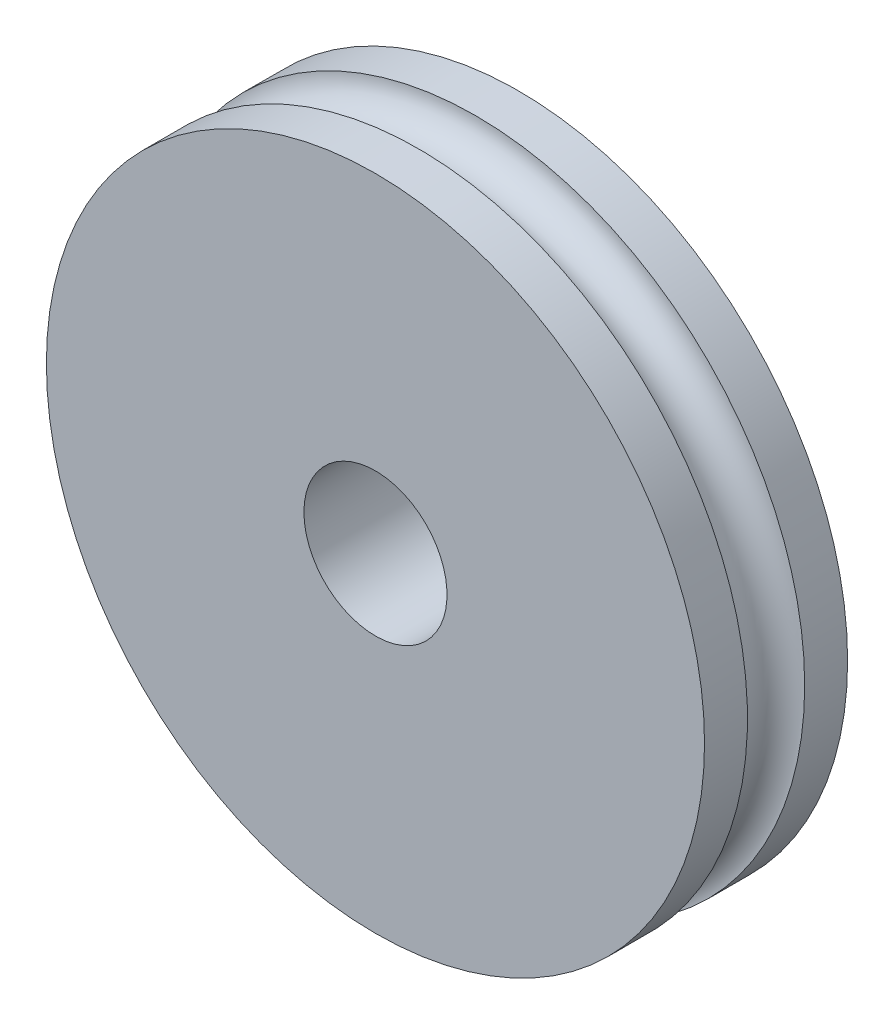
SolidWorks part; units mm, degrees
ref_plane "Front Plane" through (0, 0, 0) normal (0, 0, 1) x (1, 0, 0)
ref_plane "Top Plane" through (0, 0, 0) normal (0, 1, 0) x (1, 0, 0)
ref_plane "Right Plane" through (0, 0, 0) normal (1, 0, 0) x (0, 0, -1)
sketch "Sketch1" plane through (0, 0, 0) normal (0, 0, 1) x (1, 0, 0)
  circle A0 centre (0, 0) radius 115
  dimension "D1" = 230
extrude "Boss-Extrude1" add sketch "Sketch1" along normal blind 50
sketch "Sketch2" plane through (0, 0, 0) normal (1, 0, 0) x (0, 0, -1)
  line L0 (0, 115) -> (-50, 115) construction
  line L2 (0, 0) -> (-50, 0) construction
  line L3 (-50, 115) -> (-50, -115) construction
  line L4 (-25, 115) -> (-25, 0) construction
  circle A0 centre (-25, 115) radius 10
  dimension "D1" = 20
revolve "Cut-Revolve1" cut sketch "Sketch2" angle 360 about L2
sketch "Sketch3" plane through (0, 0, 0) normal (0, 0, -1) x (-1, 0, 0)
  circle A0 centre (0, 0) radius 25
  dimension "D1" = 50
extrude "Cut-Extrude1" cut sketch "Sketch3" against normal through all
